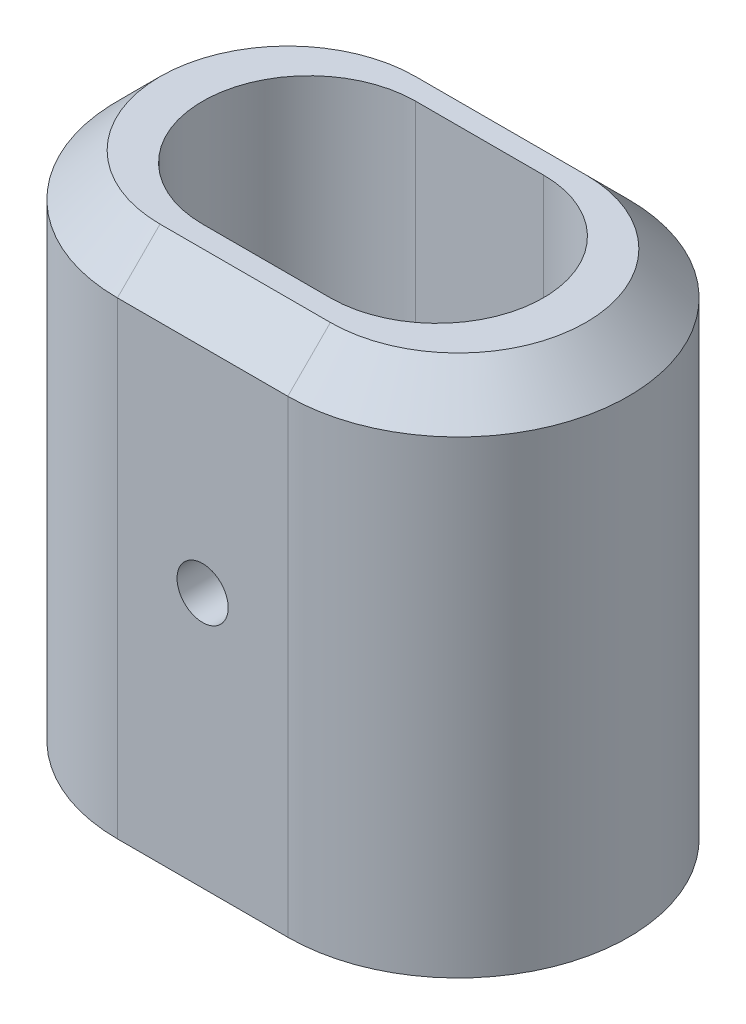
SolidWorks part; units mm, degrees
ref_plane "Front Plane" through (0, 0, 0) normal (0, 0, 1) x (1, 0, 0)
ref_plane "Top Plane" through (0, 0, 0) normal (0, 1, 0) x (1, 0, 0)
ref_plane "Right Plane" through (0, 0, 0) normal (1, 0, 0) x (0, 0, -1)
sketch "Sketch1" plane through (0, 0, 0) normal (0, 0, 1) x (1, 0, 0)
  line L1 (30, -30) -> (-30, -30)
  line L2 (30, -30) -> (30, 30)
  line L3 (30, 30) -> (-30, 30)
  line L4 (-30, -30) -> (-30, 30)
  line L5 (30, -30) -> (-30, 30) construction
  line L6 (30, 30) -> (-30, -30) construction
  point P0 (0, 0)
  dimension "D1" = 60
  dimension "D2" = 60
extrude "Boss-Extrude1" add sketch "Sketch1" along normal mid plane 40
sketch "Sketch4" plane through (0, -30, 0) normal (0, -1, 0) x (1, 0, 0)
  line L1 (30, -20) -> (-30, -20)
  line L2 (30, -20) -> (30, 20)
  line L3 (30, 20) -> (-30, 20)
  line L4 (-30, -20) -> (-30, 20)
  line L5 (30, -20) -> (-30, 20) construction
  line L6 (30, 20) -> (-30, -20) construction
  point P0 (0, 0)
  point P7 (0, 0)
  point P8 (0, 0)
sketch "Sketch5" plane through (0, -30, 0) normal (0, -1, 0) x (1, 0, 0)
  line L0 (-30, 0) -> (-10, 0) construction
  line L1 (-30, -20) -> (-30, 20) construction
  line L4 (30, 0) -> (10, 0) construction
  circle A0 centre (-10, 0) radius 20
  circle A1 centre (10, 0) radius 20
  line M4 (-30, -20) -> (30, -20)
  line M5 (30, -20) -> (30, 20)
  line M6 (30, 20) -> (-30, 20)
  line M7 (-30, 20) -> (-30, -20)
  dimension "D1" = 20
extrude "Cut-Extrude1" cut sketch "Sketch5" against normal up to surface (60 mm away) contours A1 M5 M4 | A1 M6 M5 | A0 M6 M7 | A0 M7 M4 up to face at (0, 30, 0)
chamfer "Chamfer1" distance 5 angle 45 4 edges at (0, 30, 20) (30, 30, 0) (-30, 30, 0) (0, 30, -20)
sketch "Sketch6" plane through (0, 0, -20) normal (0, 0, -1) x (-1, 0, 0)
  circle A0 centre (0, 0) radius 3
  dimension "D1" = 6
extrude "Cut-Extrude2" cut sketch "Sketch6" against normal through all
sketch "Sketch7" plane through (0, -30, 0) normal (0, -1, 0) x (1, 0, 0)
  line L0 (0, -12.5) -> (0, 12.5)
  line L3 (-19.9994, 0) -> (20.0006, 0) construction
  point P5 (0, 0)
  dimension "D1" = 40
  dimension "D2" = 25
sketch "Sketch8" plane through (0, -30, 0) normal (0, -1, 0) x (1, 0, 0)
  line L1 (20, -12.5) -> (-20, -12.5)
  line L2 (20, -12.5) -> (20, 12.5)
  line L3 (20, 12.5) -> (-20, 12.5)
  line L4 (-20, -12.5) -> (-20, 12.5)
  line L5 (20, -12.5) -> (-20, 12.5) construction
  line L6 (20, 12.5) -> (-20, -12.5) construction
  point P0 (0, 0)
  dimension "D1" = 40
  dimension "D2" = 25
sketch "Sketch9" plane through (0, -30, 0) normal (0, -1, 0) x (1, 0, 0)
  line L0 (-19.9994, 0) -> (-7.4994, 0) construction
  line L1 (-19.9994, 0) -> (20.0006, 0) construction
  line L2 (0, 12.5) -> (0, -12.5) construction
  line L4 (20, -12.5) -> (-20, -12.5)
  line L5 (20, -12.5) -> (20, 12.5)
  line L6 (20, 12.5) -> (-20, 12.5)
  line L7 (-20, -12.5) -> (-20, 12.5)
  line L8 (20, -12.5) -> (-20, 12.5) construction
  line L9 (20, 12.5) -> (-20, -12.5) construction
  circle A0 centre (-7.4994, 0) radius 12.5
  circle A1 centre (7.4994, 0) radius 12.5
  point P13 (0, 0)
  dimension "D1" = 12.5
extrude "Cut-Extrude4" cut sketch "Sketch9" against normal through all contours A0 A1 | A0 A1 L6 | A1 A0 | L4 A1 A0 | A1 A0
